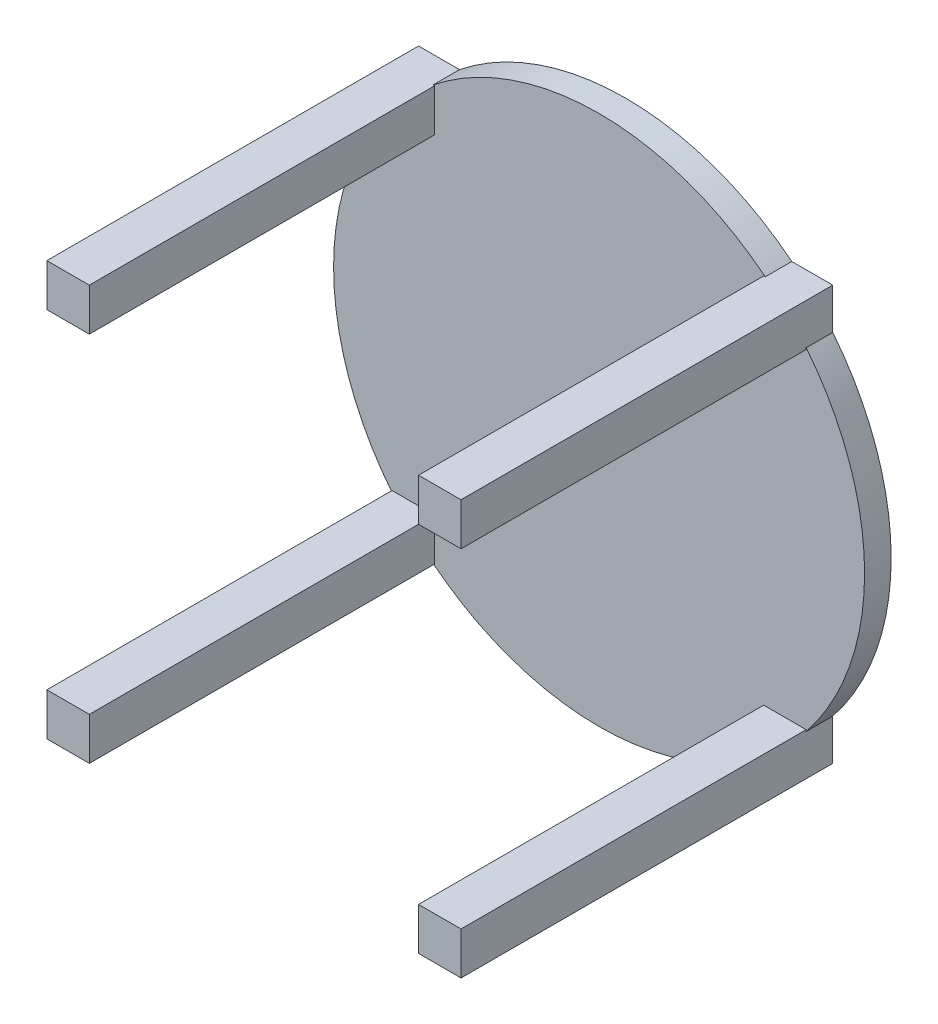
SolidWorks part; units mm, degrees
ref_plane "前视基准面" through (0, 0, 0) normal (0, 0, 1) x (1, 0, 0)
ref_plane "上视基准面" through (0, 0, 0) normal (0, 1, 0) x (1, 0, 0)
ref_plane "右视基准面" through (0, 0, 0) normal (1, 0, 0) x (0, 0, -1)
other "Configuration Table"
sketch "草图1" plane through (0, 0, 0) normal (0, 0, 1) x (1, 0, 0)
  circle A0 centre (0, 0) radius 500
extrude "凸台-拉伸1" add sketch "草图1" along normal blind 50
sketch "草图2" plane through (0, 0, 0) normal (0, 0, 1) x (1, 0, 0)
  line L1 (310, 310) -> (390, 310)
  line L2 (310, 310) -> (310, 390)
  line L3 (310, 390) -> (390, 390)
  line L4 (390, 310) -> (390, 390)
  line L5 (310, 310) -> (390, 390) construction
  line L6 (310, 390) -> (390, 310) construction
  point P0 (350, 350)
extrude "凸台-拉伸2" add sketch "草图2" along normal blind 700
sketch "草图3" plane through (0, 0, 0) normal (0, 0, 1) x (1, 0, 0)
  line L1 (-390, 310) -> (-310, 310)
  line L2 (-390, 310) -> (-390, 390)
  line L3 (-390, 390) -> (-310, 390)
  line L4 (-310, 310) -> (-310, 390)
  line L5 (-390, 310) -> (-310, 390) construction
  line L6 (-390, 390) -> (-310, 310) construction
  point P0 (-350, 350)
extrude "凸台-拉伸3" add sketch "草图3" along normal blind 700
sketch "草图4" plane through (0, 0, 0) normal (0, 0, 1) x (1, 0, 0)
  line L1 (-390, -390) -> (-310, -390)
  line L2 (-390, -390) -> (-390, -310)
  line L3 (-390, -310) -> (-310, -310)
  line L4 (-310, -390) -> (-310, -310)
  line L5 (-390, -390) -> (-310, -310) construction
  line L6 (-390, -310) -> (-310, -390) construction
  point P0 (-350, -350)
extrude "凸台-拉伸4" add sketch "草图4" along normal blind 700
sketch "草图5" plane through (0, 0, 0) normal (0, 0, 1) x (1, 0, 0)
  line L1 (310, -390) -> (390, -390)
  line L2 (310, -390) -> (310, -310)
  line L3 (310, -310) -> (390, -310)
  line L4 (390, -390) -> (390, -310)
  line L5 (310, -390) -> (390, -310) construction
  line L6 (310, -310) -> (390, -390) construction
  point P0 (350, -350)
extrude "凸台-拉伸5" add sketch "草图5" along normal blind 700
